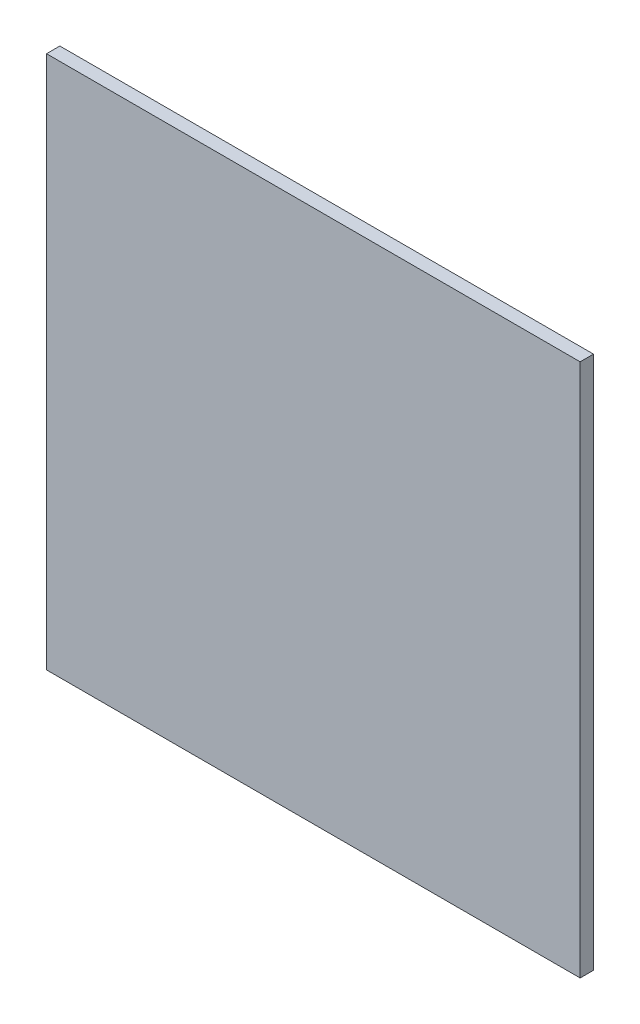
SolidWorks part; units mm, degrees
ref_plane "Front Plane" through (0, 0, 0) normal (0, 0, 1) x (1, 0, 0)
ref_plane "Top Plane" through (0, 0, 0) normal (0, 1, 0) x (1, 0, 0)
ref_plane "Right Plane" through (0, 0, 0) normal (1, 0, 0) x (0, 0, -1)
sketch "Sketch1" plane through (0, 0, 0) normal (0, 0, 1) x (1, 0, 0)
  line L1 (-100, -100) -> (100, -100)
  line L2 (-100, -100) -> (-100, 100)
  line L3 (-100, 100) -> (100, 100)
  line L4 (100, -100) -> (100, 100)
  line L5 (-100, -100) -> (100, 100) construction
  line L6 (-100, 100) -> (100, -100) construction
  point P0 (0, 0)
  dimension "D1" = 200
  dimension "D2" = 200
extrude "Boss-Extrude1" add sketch "Sketch1" along normal blind 5
